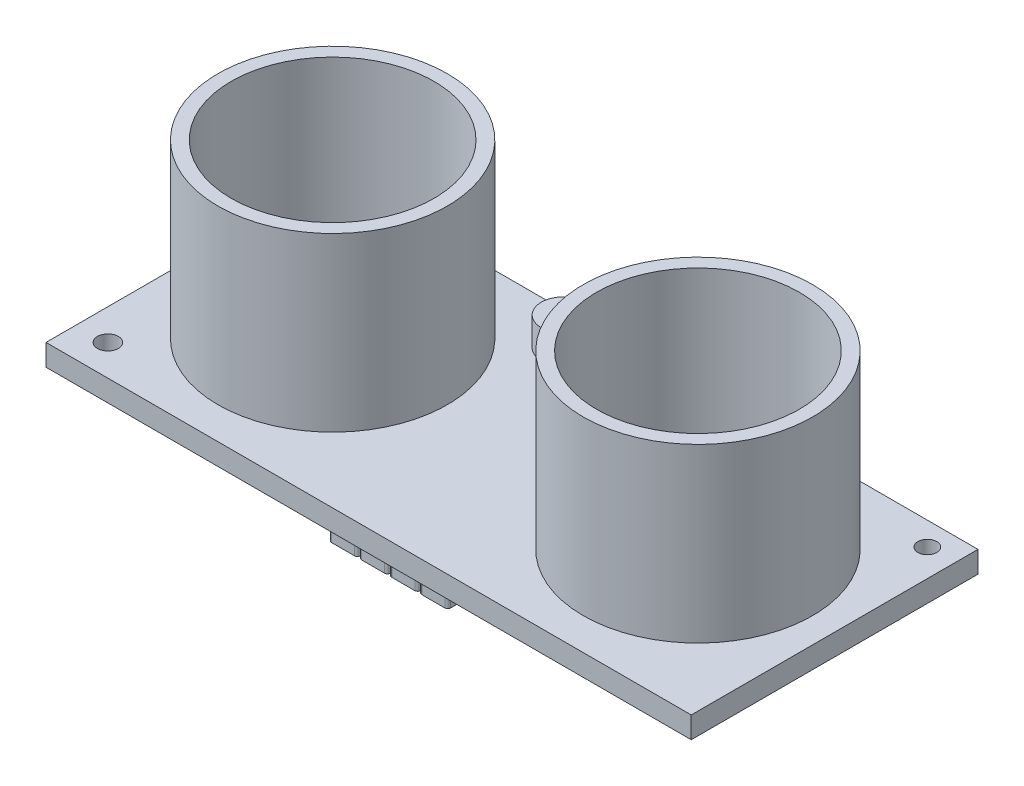
SolidWorks part; units mm, degrees
ref_plane "Front Plane" through (0, 0, 0) normal (0, 0, 1) x (1, 0, 0)
ref_plane "Top Plane" through (0, 0, 0) normal (0, 1, 0) x (1, 0, 0)
ref_plane "Right Plane" through (0, 0, 0) normal (1, 0, 0) x (0, 0, -1)
sketch "Sketch1" plane through (0, 0, 0) normal (0, 1, 0) x (1, 0, 0)
  line L5 (-9.0124, -20.621) -> (-54.0124, -20.621)
  line L8 (-9.0124, -20.621) -> (-9.0124, -40.621)
  line L11 (-9.0124, -40.621) -> (-54.0124, -40.621)
  line L12 (-54.0124, -20.621) -> (-54.0124, -40.621)
extrude "Boss-Extrude2" add sketch "Sketch1" along normal blind 1.5
sketch "Sketch2" plane through (0, 1.5, 0) normal (0, 1, 0) x (1, 0, 0)
  line L0 (-31.5124, -20.621) -> (-31.5124, -40.621) construction
  line L1 (-9.0124, -20.621) -> (-54.0124, -20.621) construction
  line L2 (-54.0124, -40.621) -> (-9.0124, -40.621) construction
  circle A0 centre (-44.2514, -30.3913) radius 8
  circle A1 centre (-44.2514, -30.3913) radius 7.0725
  circle A2 centre (-18.7734, -30.3913) radius 7.0725
  circle A3 centre (-18.7734, -30.3913) radius 8
extrude "Boss-Extrude3" add sketch "Sketch2" along normal blind 12
sketch "Sketch3" plane through (0, 1.5, 0) normal (0, 1, 0) x (1, 0, 0)
  line L0 (-31.5124, -20.621) -> (-31.5124, -40.621) construction
  line L1 (-9.0124, -20.621) -> (-54.0124, -20.621) construction
  line L2 (-54.0124, -40.621) -> (-9.0124, -40.621) construction
  line L3 (-35.6265, -22.915) -> (-27.6265, -22.915) construction
  line L4 (-35.6265, -21.3696) -> (-27.6265, -21.3696)
  line L5 (-35.6265, -24.4604) -> (-27.6265, -24.4604)
  arc A0 (-35.6265, -21.3696) -> (-35.6265, -24.4604) centre (-35.6265, -22.915) ccw
  arc A1 (-27.6265, -24.4604) -> (-27.6265, -21.3696) centre (-27.6265, -22.915) ccw
  point P8 (-31.6265, -22.915)
extrude "Boss-Extrude4" add sketch "Sketch3" along normal blind 2
sketch "Sketch4" plane through (0, 1.5, 0) normal (0, 1, 0) x (1, 0, 0)
  circle A0 centre (-51.8512, -38.465) radius 1
  circle A1 centre (-10.8047, -22.6051) radius 1
  circle A2 centre (-51.8512, -38.465) radius 0.7307
  circle A3 centre (-10.8047, -22.6051) radius 0.7307
  point P8 (0, 0)
  point P9 (0, 0)
  point P10 (0, 0)
extrude "Cut-Extrude6" cut sketch "Sketch4" against normal blind 22 contours A2
sketch "Sketch7" plane through (0, 1.5, 0) normal (0, 1, 0) x (1, 0, 0)
  circle A0 centre (-10.9211, -22.2467) radius 1
  circle A1 centre (-10.9211, -22.2467) radius 0.6604
extrude "Cut-Extrude9" cut sketch "Sketch7" against normal blind 11 contours A1
sketch "Sketch9" plane through (0, 0, 0) normal (0, -1, 0) x (1, 0, 0)
  line L0 (-9.0124, 40.621) -> (-9.0124, 20.621) construction
  line L1 (-27.3624, 37.2535) -> (-29.3624, 37.2535)
  line L2 (-27.3624, 37.2535) -> (-27.3624, 39.2535)
  line L3 (-27.3624, 39.2535) -> (-29.3624, 39.2535)
  line L4 (-29.3624, 37.2535) -> (-29.3624, 39.2535)
  dimension "D1" = 2
  dimension "D2" = 2
  dimension "D3" = 18.35
extrude "Boss-Extrude5" add sketch "Sketch9" along normal blind 2
fillet "Fillet2" radius 0.2 4 edges at (-29.3624, -1, 39.2535) (-27.3624, -1, 39.2535) (-29.3624, -1, 37.2535) (-27.3624, -1, 37.2535)
pattern_linear "LPattern1" count 4 spacing 2.1 along (-1, 0, 0) of "Fillet2", "Boss-Extrude5"
ref_plane "Plane1" through (-31.5124, 0, 0) normal (-1, 0, 0) x (0, 0, 1)
sketch "Sketch10" plane through (-31.5124, 0, 0) normal (-1, 0, 0) x (0, 0, 1)
  line L0 (19.5945, 0) -> (41.6272, 0) construction
